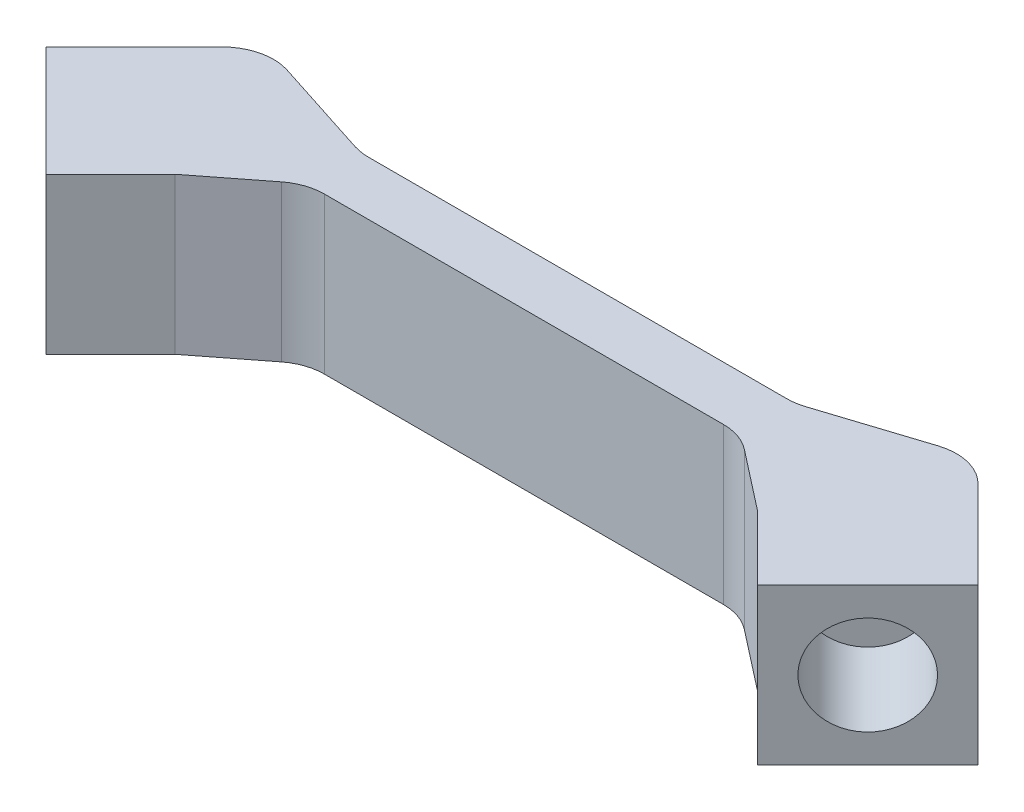
SolidWorks part; units mm, degrees
ref_plane "Front Plane" through (0, 0, 0) normal (0, 0, 1) x (1, 0, 0)
ref_plane "Top Plane" through (0, 0, 0) normal (0, 1, 0) x (1, 0, 0)
ref_plane "Right Plane" through (0, 0, 0) normal (1, 0, 0) x (0, 0, -1)
sketch "Sketch1" plane through (0, 0, 0) normal (0, 1, 0) x (1, 0, 0)
  line L0 (-8.395, 35.7208) -> (16.1076, 27.8284)
  line L5 (0, 0) -> (-15.7815, -15.7815)
  line L6 (-42.7223, 11.1592) -> (-15.7815, -15.7815)
  line L7 (71.12, 38.1) -> (71.12, 0) construction
  line L11 (-21.2689, 32.6126) -> (-42.7223, 11.1592)
  line L12 (20.0013, 27.2168) -> (122.2387, 27.2168)
  line L18 (14.5632, 11.3563) -> (0, 0)
  line L19 (22.3728, 14.0414) -> (119.8672, 14.0414)
  line L20 (142.24, 0) -> (158.0215, -15.7815)
  line L21 (127.6768, 11.3563) -> (142.24, 0)
  line L22 (150.635, 35.7208) -> (126.1324, 27.8284)
  line L23 (163.5089, 32.6126) -> (184.9623, 11.1592)
  line L24 (184.9623, 11.1592) -> (158.0215, -15.7815)
  arc A0 (22.3728, 14.0414) -> (14.5632, 11.3563) centre (22.3728, 1.3414) ccw
  arc A1 (16.1076, 27.8284) -> (20.0013, 27.2168) centre (20.0013, 39.9168) ccw
  arc A2 (-21.2689, 32.6126) -> (-8.395, 35.7208) centre (-12.2886, 23.6324) cw
  arc A3 (126.1324, 27.8284) -> (122.2387, 27.2168) centre (122.2387, 39.9168) cw
  arc A4 (119.8672, 14.0414) -> (127.6768, 11.3563) centre (119.8672, 1.3414) cw
  arc A5 (163.5089, 32.6126) -> (150.635, 35.7208) centre (154.5286, 23.6324) ccw
  point P14 (71.12, 27.2168)
  point P21 (-15.7815, 38.1)
  point P22 (71.12, 14.0414)
  dimension "D2" = 12.7
  dimension "D3" = 38.1
  dimension "D4" = 90
  dimension "D5" = 38.1
  dimension "D6" = 90
  dimension "D7" = 38.1
extrude "Boss-Extrude1" add sketch "Sketch1" along normal blind 38.1
sketch "Sketch2" plane through (-15.7815, 0, 15.7815) normal (-0.7071, 0, 0.7071) x (0.7071, 0, 0.7071)
  line L0 (-38.1, 38.1) -> (0, 0) construction
  line L1 (-38.1, 0) -> (0, 38.1) construction
  circle A0 centre (-19.05, 19.05) radius 12.065
  dimension "D1" = 24.13
extrude "Cut-Extrude1" cut sketch "Sketch2" against normal blind 25.4
sketch "Sketch7" plane through (86.9015, 0, 86.9015) normal (0.7071, 0, 0.7071) x (0.7071, 0, -0.7071)
  line L0 (119.6289, 38.1) -> (119.6289, 0) construction
  line L1 (100.5789, 38.1) -> (138.6789, 38.1) construction
  line L2 (100.5789, 0) -> (138.6789, 0) construction
  line L3 (119.6289, 0) -> (100.5789, 19.05) construction
  line L4 (100.5789, 38.1) -> (100.5789, 0) construction
  line L5 (100.5789, 19.05) -> (138.6789, 19.05) construction
  line L6 (138.6789, 38.1) -> (138.6789, 0) construction
  circle A0 centre (119.6289, 19.05) radius 12.065
  dimension "D1" = 24.13
extrude "Cut-Extrude2" cut sketch "Sketch7" against normal blind 25.4
sketch "Sketch9" plane through (0, 0, -27.2168) normal (0, 0, -1) x (-1, 0, 0)
  line L0 (-71.12, 38.1) -> (-71.12, 0) construction
  line L1 (-122.2387, 38.1) -> (-20.0013, 38.1) construction
  line L2 (-122.2387, 0) -> (-20.0013, 0) construction
  line L3 (-122.2387, 19.05) -> (-20.0013, 19.05) construction
  line L4 (-122.2387, 38.1) -> (-122.2387, 0) construction
  line L5 (-20.0013, 38.1) -> (-20.0013, 0) construction
  line L6 (-84.2645, 26.289) -> (-84.2645, 0)
  line L7 (-84.2645, 26.289) -> (-57.9755, 26.289)
  line L8 (-57.9755, 26.289) -> (-57.9755, 0)
  line L13 (-122.2387, 0) -> (-20.0013, 0)
  line L14 (-20.0013, 0) -> (-20.0013, 38.1)
  line L15 (-20.0013, 38.1) -> (-122.2387, 38.1)
  line L16 (-122.2387, 38.1) -> (-122.2387, 0)
  line L17 (-84.2645, 0) -> (-57.9755, 0)
  point P14 (-71.12, 26.289)
  dimension "D1" = 26.289
  dimension "D2" = 26.289
  dimension "D3" = 0
extrude "Boss-Extrude3" add sketch "Sketch9" along normal blind 8.89
sketch "Sketch10" plane through (0, 0, -36.1068) normal (0, 0, -1) x (-1, 0, 0)
  line L0 (-71.12, 26.289) -> (-71.12, 0) construction
  line L1 (-57.9755, 26.289) -> (-84.2645, 26.289) construction
  line L2 (-84.2645, 0) -> (-57.9755, 0) construction
  line L3 (-84.2645, 13.1445) -> (-57.9755, 13.1445) construction
  line L4 (-84.2645, 26.289) -> (-84.2645, 0) construction
  line L5 (-57.9755, 0) -> (-57.9755, 26.289) construction
  circle A0 centre (-71.12, 13.1445) radius 8.0645
  dimension "D1" = 16.129
extrude "Cut-Extrude3" cut sketch "Sketch10" against normal blind 6.35
sketch "Sketch12" plane through (0, 0, -29.7568) normal (0, 0, -1) x (-1, 0, 0)
  line L0 (-71.12, 21.209) -> (-71.12, 5.08) construction
  circle A0 centre (-71.12, 13.1445) radius 8.0645 construction
  circle A1 centre (-71.12, 13.1445) radius 8.0645 construction
  circle A2 centre (-71.12, 13.1445) radius 6.35
  dimension "D1" = 12.7
extrude "Cut-Extrude5" cut sketch "Sketch12" against normal blind 5.08
fillet "Fillet1" radius 12.7 2 edges at (57.9755, 26.289, -31.6618) (84.2645, 26.289, -31.6618)
